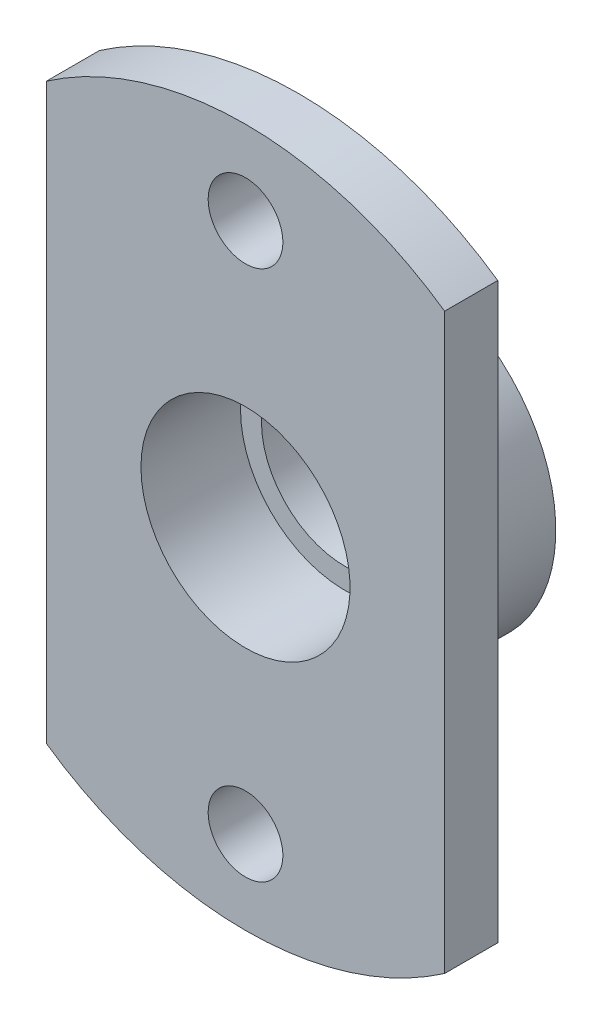
SolidWorks part; units mm, degrees
ref_plane "Front Plane" through (0, 0, 0) normal (0, 0, 1) x (1, 0, 0)
ref_plane "Top Plane" through (0, 0, 0) normal (0, 1, 0) x (1, 0, 0)
ref_plane "Right Plane" through (0, 0, 0) normal (1, 0, 0) x (0, 0, -1)
sketch "Sketch1" plane through (0, 0, 0) normal (0, 1, 0) x (1, 0, 0)
  line L0 (0, 0) -> (-11.7, 0)
  line L1 (-11.7, 0) -> (-11.7, 4.7625)
  line L2 (-11.7, 4.7625) -> (-12.7, 4.7625)
  line L3 (-12.7, 4.7625) -> (-12.7, 7.3025)
  line L4 (-12.7, 7.3025) -> (-9.16, 7.3025)
  line L5 (-9.16, 7.3025) -> (-9.16, 2.54)
  line L6 (-9.16, 2.54) -> (0, 2.54)
  line L7 (0, 2.54) -> (0, 0)
  line L8 (-16.7, 8.7445) -> (-16.7, -4.7363) construction
  dimension "D1" = 1
  dimension "D2" = 4.7625
  dimension "D3" = 2.54
  dimension "D4" = 2.54
  dimension "D5" = 2.54
  dimension "D6" = 12.7
  dimension "D7" = 10
revolve "Revolve1" add sketch "Sketch1" angle 360 about L8
sketch "Sketch2" plane through (0, 0, -7.3025) normal (0, 0, -1) x (-1, 0, 0)
  line L0 (26.225, 0) -> (16.7, 0) construction
  line L1 (26.225, -15.875) -> (51.625, -15.875)
  line L2 (26.225, -15.875) -> (26.225, 15.875)
  line L3 (26.225, 15.875) -> (51.625, 15.875)
  line L4 (51.625, -15.875) -> (51.625, 15.875)
  line L5 (7.175, -15.875) -> (-18.225, -15.875)
  line L6 (7.175, -15.875) -> (7.175, 15.875)
  line L7 (7.175, 15.875) -> (-18.225, 15.875)
  line L8 (-18.225, -15.875) -> (-18.225, 15.875)
  line L9 (16.7, 0) -> (7.175, 0) construction
  line L10 (16.7, -12.7) -> (16.7, 0) construction
  line L11 (16.7, 12.7) -> (16.7, 0) construction
  circle A1 centre (16.7, -12.7) radius 1.7859
  circle A3 centre (16.7, 12.7) radius 1.7859
  dimension "D1" = 19.05
  dimension "D4" = 3.5719
  dimension "D6" = 3.5719
  dimension "D2" = 31.75
  dimension "D3" = 25.4
  dimension "D5" = 12.7
extrude "Cut-Extrude1" cut sketch "Sketch2" against normal up to surface (7.3025 mm away) up to face at (-33.4, 0, 0)
